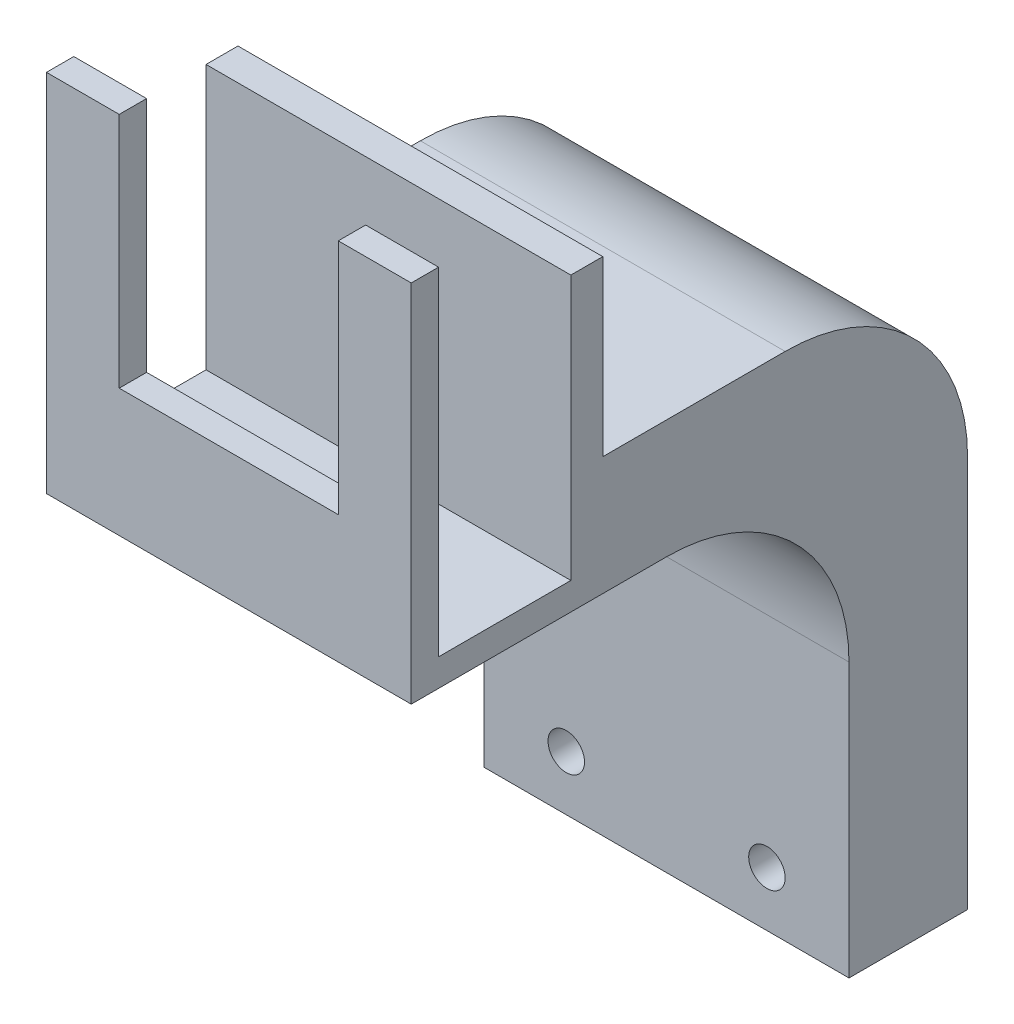
SolidWorks part; units mm, degrees
ref_plane "前视基准面" through (0, 0, 0) normal (0, 0, 1) x (1, 0, 0)
ref_plane "上视基准面" through (0, 0, 0) normal (0, 1, 0) x (1, 0, 0)
ref_plane "右视基准面" through (0, 0, 0) normal (1, 0, 0) x (0, 0, -1)
sketch "草图1" plane through (0, 0, 0) normal (0, 0, 1) x (1, 0, 0)
  line L0 (0, 0) -> (40, 0)
  line L1 (40, 0) -> (40, 40)
  line L2 (40, 40) -> (0, 40)
  line L3 (0, 40) -> (0, 0)
  dimension "D1" = 40
  dimension "D2" = 40
  dimension "D3" = 40
extrude "凸台-拉伸1" add sketch "草图1" along normal blind 21
sketch "草图2" plane through (40, 0, 0) normal (1, 0, 0) x (0, 0, -1)
  line L0 (-3.5, 40) -> (-3.5, 3)
  line L1 (-21, 40) -> (0, 40) construction
  line L2 (-3.5, 3) -> (-18, 3)
  line L3 (-18, 3) -> (-18, 40)
  line L4 (-18, 40) -> (-3.5, 40)
  line L5 (0, 0) -> (0, 40) construction
  line L6 (-21, 0) -> (-21, 40) construction
  dimension "D1" = 3.5
  dimension "D2" = 3
  dimension "D3" = 37
extrude "切除-拉伸1" cut sketch "草图2" against normal through all
sketch "草图3" plane through (0, 0, 21) normal (0, 0, 1) x (1, 0, 0)
  line L0 (7.9822, 14) -> (7.9822, 40)
  line L1 (40, 40) -> (0, 40) construction
  line L2 (7.9822, 40) -> (32, 40)
  line L3 (32, 40) -> (32, 14)
  line L5 (7.9822, 14) -> (32, 14)
  line L9 (0, 40) -> (0, 0)
  line L10 (0, 0) -> (40, 0)
  line L11 (40, 0) -> (40, 40)
  line L12 (40, 40) -> (0, 40)
  line L13 (0, 40) -> (0, 0)
  line L14 (0, 0) -> (40, 0)
  line L15 (40, 0) -> (40, 40)
  line L16 (40, 40) -> (0, 40)
  dimension "D1" = 26
  dimension "D2" = 26
  dimension "D4" = 0
extrude "切除-拉伸2" cut sketch "草图3" against normal up to next
sketch "草图4" plane through (0, 0, 0) normal (0, 0, -1) x (-1, 0, 0)
  line L0 (-40, 32) -> (0, 32)
  line L1 (-40, 0) -> (-40, 40) construction
  line L2 (0, 40) -> (0, 0) construction
  line L3 (0, 32) -> (0, 40)
  line L4 (0, 40) -> (-40, 40)
  line L5 (-40, 40) -> (-40, 32)
  dimension "D1" = 8
extrude "切除-拉伸3" cut sketch "草图4" against normal blind 16
sketch "草图5" plane through (0, 0, 0) normal (0, 0, -1) x (-1, 0, 0)
  line L0 (-40, 0) -> (-40, 32) construction
  line L3 (-40, 0) -> (0, 0)
  line L5 (-40, 13) -> (0, 13)
  line L6 (-40, 13) -> (-40, 0)
  line L7 (-40, 0) -> (0, 0)
  line L8 (0, 13) -> (0, 0)
  line M5 (0, 0) -> (0, 32)
  line M7 (-40, 32) -> (-40, 0)
  line M8 (-40, 0) -> (0, 0)
  dimension "D1" = 13
extrude "凸台-拉伸3" add sketch "草图5" along normal blind 40 contours L5 M7 M8 M5
sketch "草图6" plane through (0, 0, 0) normal (0, -1, 0) x (1, 0, 0)
  line L0 (0, 21) -> (0, -40) construction
  line L1 (0, -27) -> (40, -27)
  line L2 (0, -27) -> (0, -40)
  line L3 (0, -40) -> (40, -40)
  line L4 (40, -27) -> (40, -40)
  dimension "D1" = 13
extrude "凸台-拉伸4" add sketch "草图6" along normal blind 50
fillet "圆角1" radius 20 1 edges at (20, 0, -27)
fillet "圆角2" radius 20 1 edges at (20, 13, -40)
sketch "草图7" plane through (0, 0, -40) normal (0, 0, -1) x (-1, 0, 0)
  line L0 (-40, -7) -> (-40, -50) construction
  line L1 (0, -50) -> (0, -7) construction
  line L2 (0, -50) -> (-40, -50) construction
  circle A0 centre (-31, -44) radius 2
  circle A1 centre (-9, -44) radius 2
  point P4 (0, 0)
  dimension "D1" = 4
  dimension "D2" = 4
  dimension "D3" = 9
  dimension "D4" = 9
  dimension "D5" = 6
  dimension "D6" = 6
extrude "切除-拉伸4" cut sketch "草图7" against normal up to next
